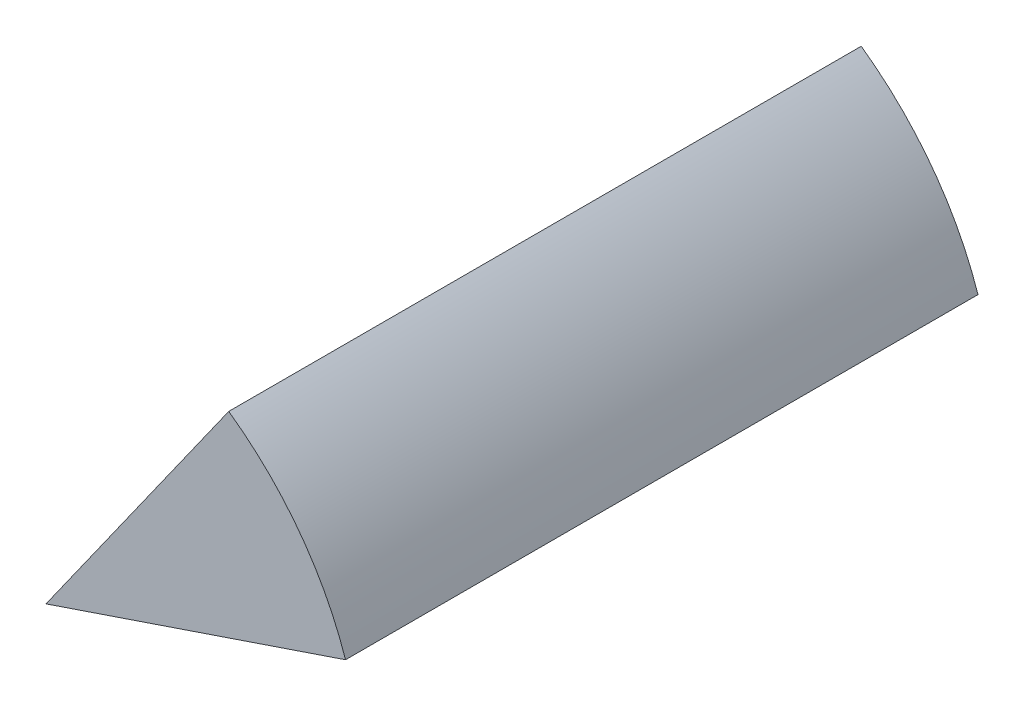
SolidWorks part; units mm, degrees
ref_plane "Alzado" through (0, 0, 0) normal (0, 0, 1) x (1, 0, 0)
ref_plane "Planta" through (0, 0, 0) normal (0, 1, 0) x (1, 0, 0)
ref_plane "Vista lateral" through (0, 0, 0) normal (1, 0, 0) x (0, 0, -1)
sketch "Croquis1" plane through (0, 0, 0) normal (0, 0, 1) x (1, 0, 0)
  line L1 (0, 0) -> (14.4479, 20.4024)
  line L2 (0, 0) -> (23.6808, 8.0136)
  arc A0 (23.6808, 8.0136) -> (14.4479, 20.4024) centre (0, 0) ccw
  dimension "D1" = 50
  dimension "D2" = 36
extrude "Saliente-Extruir1" add sketch "Croquis1" along normal blind 50
sketch "Croquis2" plane through (0, 0, 0) normal (0, 0, -1) x (-1, 0, 0)
  circle A0 centre (-14.9449, 11.3343) radius 4.9875
extrude "Cortar-Extruir1" cut sketch "Croquis2" against normal blind 10 contours A0
